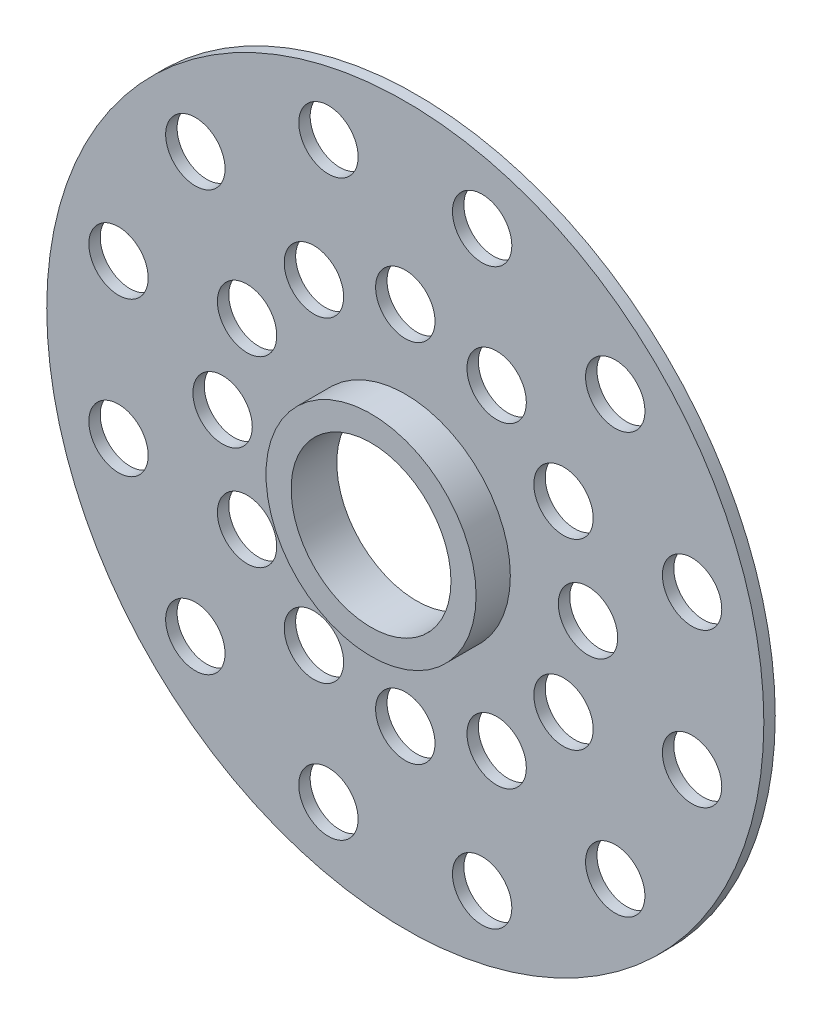
SolidWorks part; units mm, degrees
ref_plane "Спереди" through (0, 0, 0) normal (0, 0, 1) x (1, 0, 0)
ref_plane "Сверху" through (0, 0, 0) normal (0, 1, 0) x (1, 0, 0)
ref_plane "Справа" through (0, 0, 0) normal (1, 0, 0) x (0, 0, -1)
sketch "Эскиз1" plane through (0, 0, 0) normal (0, 0, 1) x (1, 0, 0)
  circle A0 centre (0, 0) radius 78.5
  circle A1 centre (0, 0) radius 17.5
extrude "Rear_cover_reference" add sketch "Эскиз1" along normal blind 2.5 from offset 47
sketch "Эскиз2" plane through (0, 0, 0) normal (0, 0, 1) x (1, 0, 0)
  circle A0 centre (0, 0) radius 23
  circle A1 centre (0, 0) radius 17.5
extrude "Bearing_boss_reference" add sketch "Эскиз2" along normal blind 10 from offset 47
sketch "Эскиз3" plane through (0, 0, 0) normal (0, 0, 1) x (1, 0, 0)
  circle A0 centre (40, 0) radius 6.5
  circle A1 centre (34.641, 20) radius 6.5
  circle A2 centre (20, 34.641) radius 6.5
  circle A3 centre (0, 40) radius 6.5
  circle A4 centre (-20, 34.641) radius 6.5
  circle A5 centre (-34.641, 20) radius 6.5
  circle A6 centre (-40, 0) radius 6.5
  circle A7 centre (-34.641, -20) radius 6.5
  circle A8 centre (-20, -34.641) radius 6.5
  circle A9 centre (0, -40) radius 6.5
  circle A10 centre (20, -34.641) radius 6.5
  circle A11 centre (34.641, -20) radius 6.5
  circle A12 centre (62.7852, 16.8232) radius 6.5
  circle A13 centre (45.9619, 45.9619) radius 6.5
  circle A14 centre (16.8232, 62.7852) radius 6.5
  circle A15 centre (-16.8232, 62.7852) radius 6.5
  circle A16 centre (-45.9619, 45.9619) radius 6.5
  circle A17 centre (-62.7852, 16.8232) radius 6.5
  circle A18 centre (-62.7852, -16.8232) radius 6.5
  circle A19 centre (-45.9619, -45.9619) radius 6.5
  circle A20 centre (-16.8232, -62.7852) radius 6.5
  circle A21 centre (16.8232, -62.7852) radius 6.5
  circle A22 centre (45.9619, -45.9619) radius 6.5
  circle A23 centre (62.7852, -16.8232) radius 6.5
extrude "Through_holes" cut sketch "Эскиз3" against normal mid plane 200
